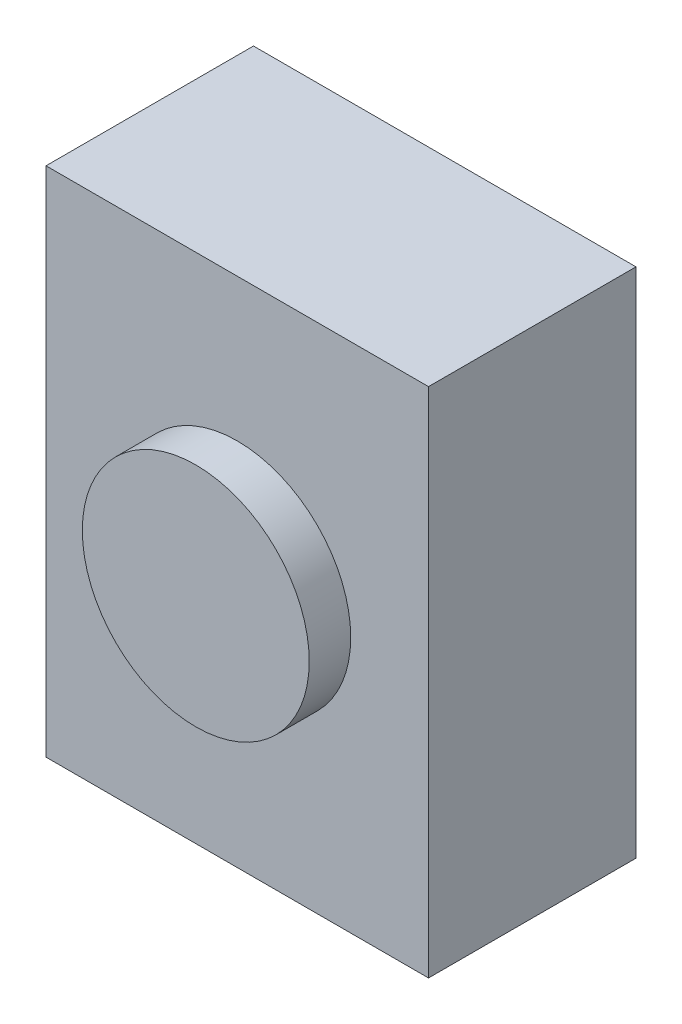
SolidWorks part; units mm, degrees
ref_plane "Front Plane" through (0, 0, 0) normal (0, 0, 1) x (1, 0, 0)
ref_plane "Top Plane" through (0, 0, 0) normal (0, 1, 0) x (1, 0, 0)
ref_plane "Right Plane" through (0, 0, 0) normal (1, 0, 0) x (0, 0, -1)
sketch "Sketch1" plane through (0, 0, 0) normal (0, 0, 1) x (1, 0, 0)
  line L1 (-1.475, -1.975) -> (1.475, -1.975)
  line L2 (-1.475, -1.975) -> (-1.475, 1.975)
  line L3 (-1.475, 1.975) -> (1.475, 1.975)
  line L4 (1.475, -1.975) -> (1.475, 1.975)
  line L5 (-1.475, -1.975) -> (1.475, 1.975) construction
  line L6 (-1.475, 1.975) -> (1.475, -1.975) construction
  point P0 (0, 0)
  dimension "D1" = 3.95
  dimension "D2" = 2.95
extrude "Boss-Extrude1" add sketch "Sketch1" along normal blind 1.6
sketch "Sketch2" plane through (0, 0, 1.6) normal (0, 0, 1) x (1, 0, 0)
  circle A0 centre (0, 0) radius 0.875
  dimension "D1" = 1.75
extrude "Boss-Extrude2" add sketch "Sketch2" along normal blind 0.32
